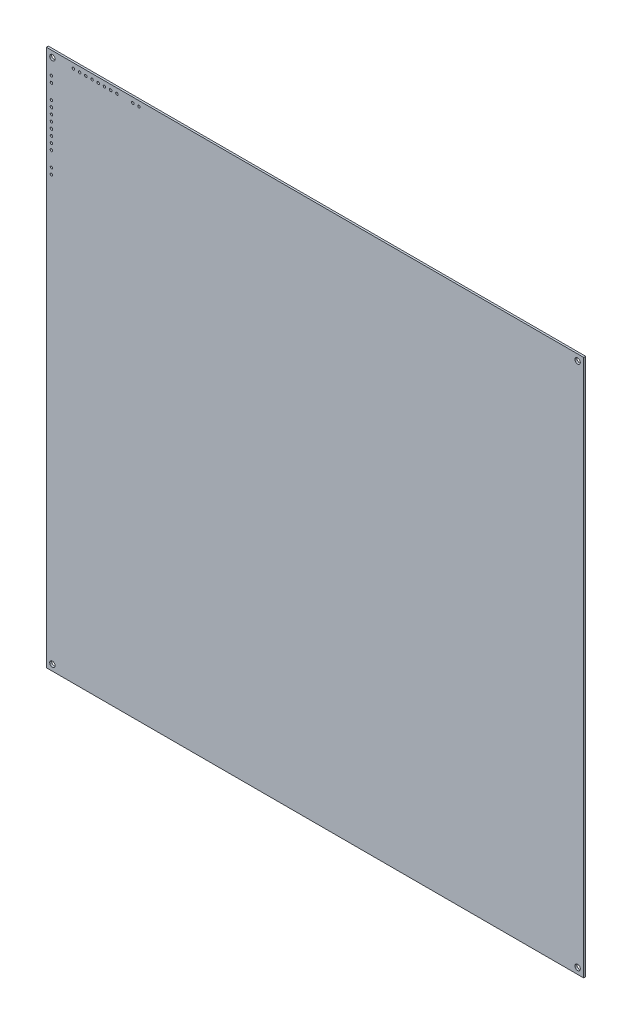
SolidWorks part; units mm, degrees
ref_plane "Front Plane" through (0, 0, 0) normal (0, 0, 1) x (1, 0, 0)
ref_plane "Top Plane" through (0, 0, 0) normal (0, 1, 0) x (1, 0, 0)
ref_plane "Right Plane" through (0, 0, 0) normal (1, 0, 0) x (0, 0, -1)
ref_plane "Plane1" through (0, 0, 1.6) normal (0, 0, 1) x (1, 0, 0)
sketch "Sketch1" plane through (0, 0, 1.6) normal (0, 0, 1) x (1, 0, 0)
  line L0 (220, -220) -> (220, 0)
  line L1 (220, 0) -> (0, 0)
  line L2 (0, 0) -> (0, -220)
  line L3 (0, -220) -> (220, -220)
  circle A0 centre (217.5, -217.5) radius 1.1
  circle A1 centre (2.1, -44.14) radius 0.5
  circle A2 centre (2.5, -217.5) radius 1.1
  circle A3 centre (2.1, -11.6) radius 0.5
  circle A4 centre (2.1, -9.06) radius 0.5
  circle A5 centre (2.1, -17.72) radius 0.5
  circle A6 centre (2.1, -20.26) radius 0.5
  circle A7 centre (2.1, -27.88) radius 0.5
  circle A8 centre (2.1, -30.42) radius 0.5
  circle A9 centre (2.1, -25.34) radius 0.5
  circle A10 centre (2.1, -22.8) radius 0.5
  circle A11 centre (2.1, -32.96) radius 0.5
  circle A12 centre (2.1, -35.5) radius 0.5
  circle A13 centre (2.1, -41.6) radius 0.5
  circle A14 centre (11.1, -2.1) radius 0.5
  circle A15 centre (2.5, -2.5) radius 1.1
  circle A16 centre (217.5, -2.5) radius 1.1
  circle A17 centre (37.94, -2.1) radius 0.5
  circle A18 centre (35.4, -2.1) radius 0.5
  circle A19 centre (28.88, -2.1) radius 0.5
  circle A20 centre (21.26, -2.1) radius 0.5
  circle A21 centre (23.8, -2.1) radius 0.5
  circle A22 centre (26.34, -2.1) radius 0.5
  circle A23 centre (16.18, -2.1) radius 0.5
  circle A24 centre (18.72, -2.1) radius 0.5
  circle A25 centre (13.64, -2.1) radius 0.5
extrude "Boss-Extrude1" add sketch "Sketch1" against normal blind 0.8
